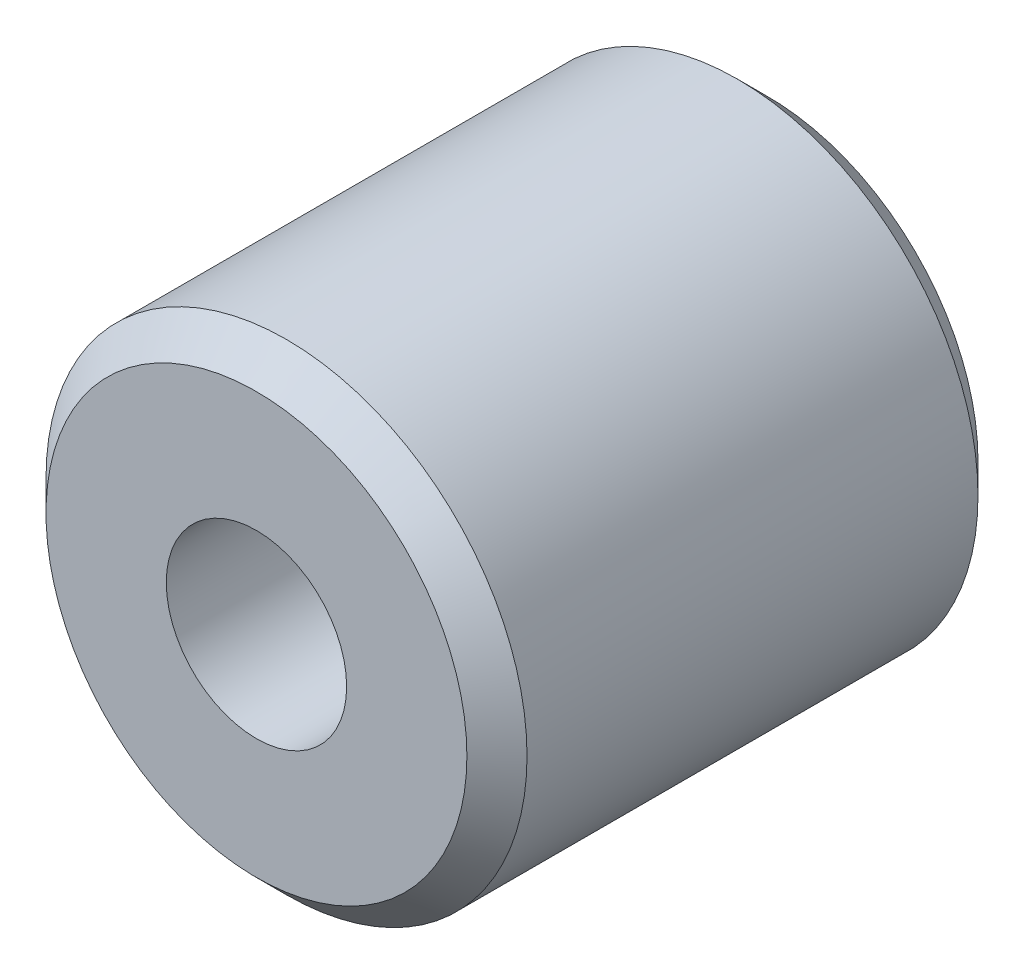
SolidWorks part; units mm, degrees
ref_plane "Front Plane" through (0, 0, 0) normal (0, 0, 1) x (1, 0, 0)
ref_plane "Top Plane" through (0, 0, 0) normal (0, 1, 0) x (1, 0, 0)
ref_plane "Right Plane" through (0, 0, 0) normal (1, 0, 0) x (0, 0, -1)
sketch "Sketch1" plane through (0, 0, 0) normal (0, 0, 1) x (1, 0, 0)
  circle A0 centre (0, 0) radius 1.5
  circle A1 centre (0, 0) radius 4
  dimension "D1" = 3
  dimension "D2" = 8
extrude "Boss-Extrude1" add sketch "Sketch1" against normal blind 8.5
chamfer "Chamfer1" distance 0.5 angle 45 2 edges at (4, 0, 0) (4, 0, -8.5)
